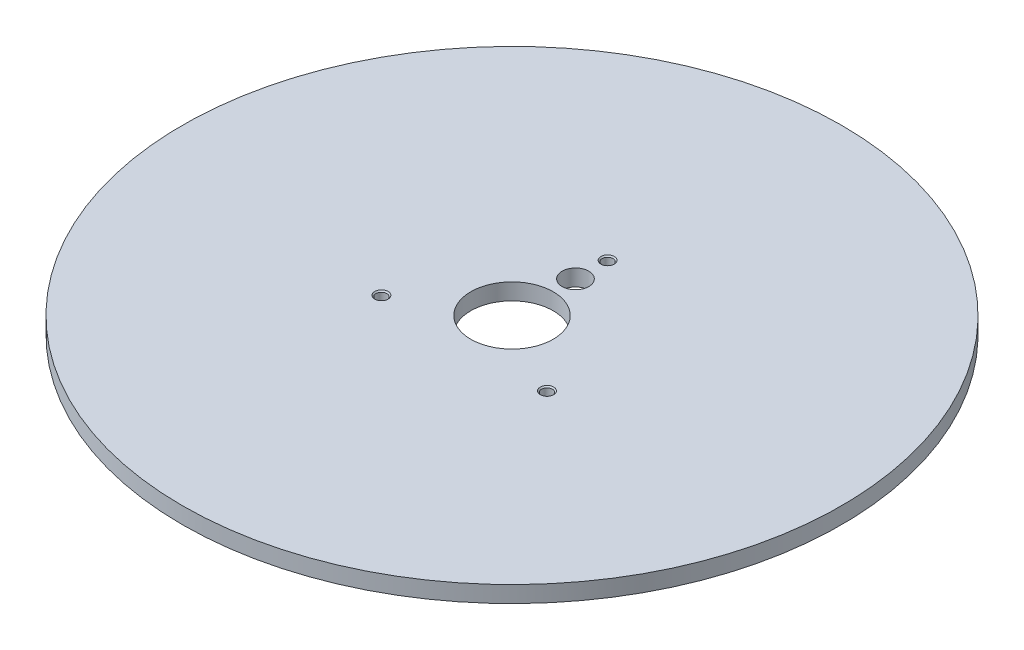
SolidWorks part; units mm, degrees
material "A-玻璃纤维"
ref_plane "前视基准面" through (0, 0, 0) normal (0, 0, 1) x (1, 0, 0)
ref_plane "上视基准面" through (0, 0, 0) normal (0, 1, 0) x (1, 0, 0)
ref_plane "右视基准面" through (0, 0, 0) normal (1, 0, 0) x (0, 0, -1)
sketch "草图1" plane through (0, 0, 0) normal (0, 1, 0) x (1, 0, 0)
  circle A0 centre (0, 0) radius 100
  dimension "D1" = 200
extrude "凸台-拉伸1" add sketch "草图1" along normal blind 5
sketch "草图2" plane through (0, 5, 0) normal (0, 1, 0) x (1, 0, 0)
  line L0 (0, 0) -> (0, 29) construction
  line L1 (0, 0) -> (25.1147, -14.5) construction
  line L2 (0, 0) -> (-25.1147, -14.5) construction
  circle A0 centre (0, 0) radius 12.5
  circle A1 centre (0, 0) radius 29 construction
  circle A2 centre (0, 0) radius 19.25 construction
  circle A3 centre (0, 19.25) radius 4.05
  point P8 (0, 29)
  point P9 (-25.1147, -14.5)
  point P10 (25.1147, -14.5)
  dimension "D1" = 25
  dimension "D2" = 58
  dimension "D5" = 38.5
  dimension "D6" = 8.1
  dimension "D3" = 120
  dimension "D4" = 120
extrude "切除-拉伸1" cut sketch "草图2" against normal up to next
sketch "草图3" plane through (0, 5, 0) normal (0, 1, 0) x (1, 0, 0)
  line L0 (0, 0) -> (0, 29) construction
  line L1 (0, 0) -> (25.1147, -14.5) construction
  line L2 (0, 0) -> (-25.1147, -14.5) construction
  circle A0 centre (0, 0) radius 29 construction
  point P7 (0, 29)
  point P8 (-25.1147, -14.5)
  point P9 (25.1147, -14.5)
  dimension "D1" = 58
  dimension "D2" = 120
  dimension "D3" = 120
hole_wizard "M4 螺纹孔1" positions "草图3" profile "草图4" tap size "M4" standard "GB" end condition through all
sketch "草图4" plane through (25.1147, 5, 14.5) normal (1, 0, 0) x (0, 0, 1)
  line L0 (0, 0) -> (0, 5)
  line L1 (0, 5) -> (1.65, 5)
  line L2 (1.65, 5) -> (1.65, 0.375)
  line L3 (1.65, 0.375) -> (2.025, 0)
  line L5 (2.025, 0) -> (0, 0)
  line L6 (-1.65, 0.375) -> (-2.025, 0) construction
  line L11 (0, -6.35) -> (0, 107.95) construction
  dimension "通孔螺纹孔钻头直径" = 3.3
  dimension "通孔螺纹孔钻头深度" = 5
  dimension "近端锥形沉头孔直径" = 4.05
  dimension "近端锥形沉头孔角度" = 90
cosmetic thread "孔螺纹线1" parameters "D2"=4
cosmetic thread "孔螺纹线2" parameters "D2"=4
cosmetic thread "孔螺纹线3" parameters "D2"=4
